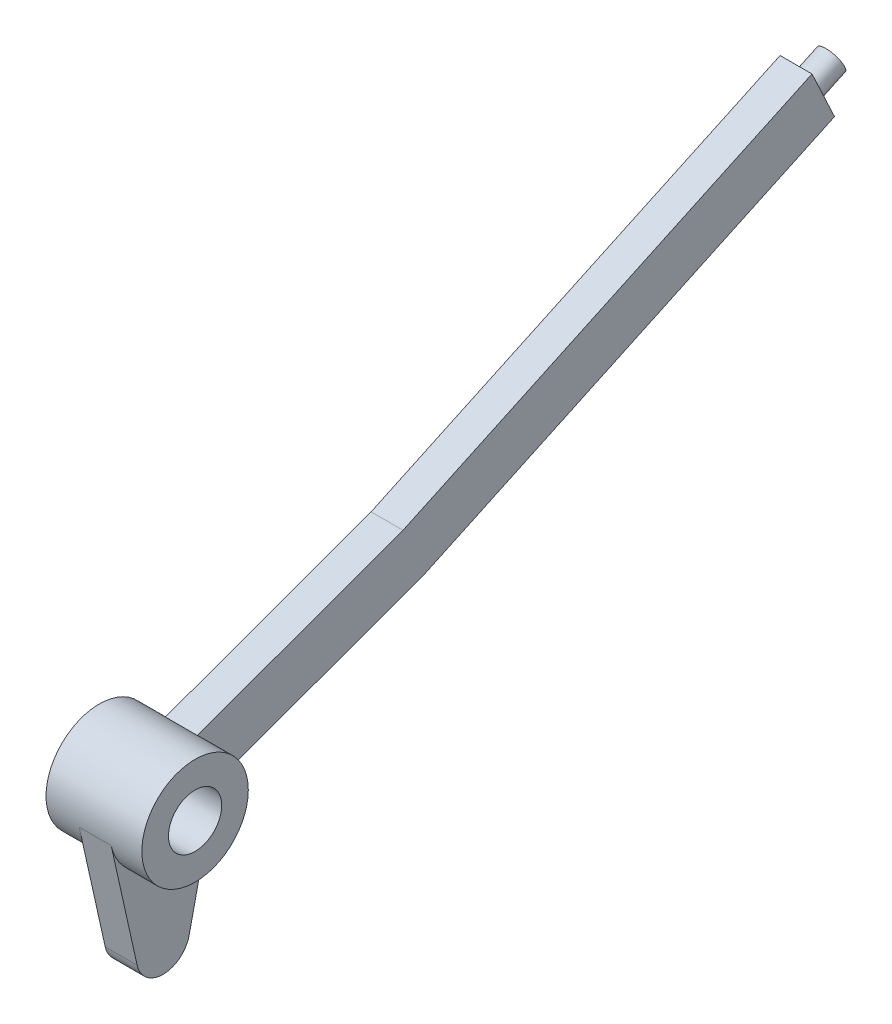
SolidWorks part; units mm, degrees
ref_plane "前视基准面" through (0, 0, 0) normal (0, 0, 1) x (1, 0, 0)
ref_plane "上视基准面" through (0, 0, 0) normal (0, 1, 0) x (1, 0, 0)
ref_plane "右视基准面" through (0, 0, 0) normal (1, 0, 0) x (0, 0, -1)
sketch "草图1" plane through (0, 0, 0) normal (1, 0, 0) x (0, 0, -1)
  circle A0 centre (0, 0) radius 10
  circle A1 centre (0, 0) radius 5
  dimension "D1" = 20
  dimension "D2" = 10
extrude "凸台-拉伸1" add sketch "草图1" along normal mid plane 18
sketch "草图2" plane through (0, 0, 0) normal (1, 0, 0) x (0, 0, -1)
  line L0 (0, 0) -> (9.3969, 3.4202) construction
  line L1 (10, 0) -> (0, 0) construction
  line L2 (9.3969, 3.4202) -> (46.9846, 17.101) construction
  line L3 (46.9846, 17.101) -> (124.0208, 53.0236) construction
  line L4 (9.8481, -1.7365) -> (48.8999, 12.4772)
  line L5 (48.8999, 12.4772) -> (126.1339, 48.492)
  line L6 (6.4279, 7.6604) -> (45.0694, 21.7248)
  line L7 (45.0694, 21.7248) -> (121.9077, 57.5551)
  line L8 (7.6868, 8.1187) -> (45.0694, 21.7248) construction
  line L9 (11.107, -1.2783) -> (48.8999, 12.4772) construction
  line L10 (121.9077, 57.5551) -> (126.1339, 48.492)
  circle A0 centre (0, 0) radius 10 construction
  arc A1 (9.8481, -1.7365) -> (6.4279, 7.6604) centre (0, 0) ccw
  dimension "D1" = 20
  dimension "D2" = 25
  dimension "D3" = 50
  dimension "D4" = 85
  dimension "D5" = 5
  dimension "D6" = 5
extrude "凸台-拉伸2" add sketch "草图2" along normal mid plane 6
sketch "草图3" plane through (0, 0, 0) normal (1, 0, 0) x (0, 0, -1)
  line L0 (-4.8804, -24.087) -> (-9.7608, -2.1739)
  line L1 (4.8804, -24.087) -> (9.7608, -2.1739)
  line L2 (0, -23) -> (0, 0) construction
  arc A0 (-4.8804, -24.087) -> (4.8804, -24.087) centre (0, -23) ccw
  circle A1 centre (0, 0) radius 10 construction
  circle A3 centre (0, 0) radius 10
  circle A4 centre (0, 0) radius 10
  dimension "D1" = 10
  dimension "D2" = 23
  dimension "D3" = 0
extrude "凸台-拉伸3" add sketch "草图3" along normal mid plane 6
sketch "草图4" plane through (0, 0, 0) normal (1, 0, 0) x (0, 0, -1)
  line L0 (9.8481, -1.7365) -> (48.8999, 12.4772) construction
  line L1 (4.8804, -24.087) -> (9.7608, -2.1739) construction
  line L2 (-9.7608, -2.1739) -> (-4.8804, -24.087) construction
  line L3 (48.8999, 12.4772) -> (126.1339, 48.492) construction
  line L4 (126.1339, 48.492) -> (121.9077, 57.5551) construction
  line L5 (121.9077, 57.5551) -> (45.0694, 21.7248) construction
  line L6 (45.0694, 21.7248) -> (6.4279, 7.6604) construction
  line L7 (4.8804, -24.087) -> (9.7608, -2.1739)
  line L8 (-9.7608, -2.1739) -> (-4.8804, -24.087)
  line L9 (48.8999, 12.4772) -> (126.1339, 48.492)
  line L10 (126.1339, 48.492) -> (121.9077, 57.5551)
  line L11 (121.9077, 57.5551) -> (45.0694, 21.7248)
  line L12 (45.0694, 21.7248) -> (6.4279, 7.6604)
  line L13 (9.8481, -1.7365) -> (48.8999, 12.4772)
  arc A0 (9.2635, -4.4068) -> (12.4339, -0.7953) centre (14.144, -5.4938) cw
  arc A1 (-9.7608, -2.1739) -> (9.7608, -2.1739) centre (0, 0) ccw construction
  arc A2 (-4.8804, -24.087) -> (4.8804, -24.087) centre (0, -23) ccw construction
  circle A3 centre (0, 0) radius 10 construction
  arc A4 (9.8481, -1.7365) -> (6.4279, 7.6604) centre (0, 0) ccw construction
  arc A5 (-9.7608, -2.1739) -> (9.7608, -2.1739) centre (0, 0) ccw
  arc A6 (-4.8804, -24.087) -> (4.8804, -24.087) centre (0, -23) ccw
  circle A7 centre (0, 0) radius 10
  arc A8 (9.8481, -1.7365) -> (6.4279, 7.6604) centre (0, 0) ccw
  dimension "D1" = 5
extrude "凸台-拉伸4" add sketch "草图4" along normal mid plane 6 contours A7 L7 A0 L13
sketch "草图5" plane through (0, 56.9731, -122.1791) normal (0, 0.4226, -0.9063) x (-1, 0, 0)
  line L0 (0, 0) -> (0, -4.3578) construction
  line L1 (3, -4.3578) -> (-3, -4.3578) construction
  line L2 (3, -9.3578) -> (3, 0.6422) construction
  line L3 (-3, -9.3578) -> (-3, 0.6422) construction
  circle A0 centre (0, -4.3578) radius 2.5
  point P10 (0, 0)
  dimension "D1" = 5
extrude "凸台-拉伸5" add sketch "草图5" along normal blind 5
